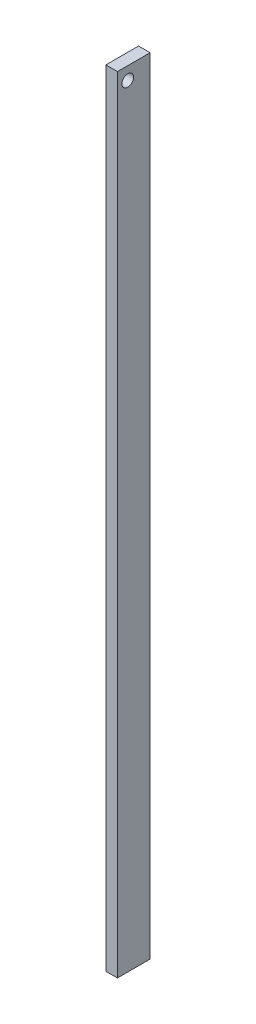
SolidWorks part; units mm, degrees
ref_plane "Alzado" through (0, 0, 0) normal (0, 0, 1) x (1, 0, 0)
ref_plane "Planta" through (0, 0, 0) normal (0, 1, 0) x (1, 0, 0)
ref_plane "Vista lateral" through (0, 0, 0) normal (1, 0, 0) x (0, 0, -1)
sketch "Sketch1" plane through (0, 0, 0) normal (0, 1, 0) x (1, 0, 0)
  line L1 (0, 0) -> (4.5, 0)
  line L2 (0, 0) -> (0, 12.7)
  line L3 (0, 12.7) -> (4.5, 12.7)
  line L4 (4.5, 0) -> (4.5, 12.7)
  dimension "D1" = 12.7
  dimension "D2" = 4.5
extrude "Boss-Extrude1" add sketch "Sketch1" along normal blind 304.8
sketch "Sketch3" plane through (0, 0, 0) normal (-1, 0, 0) x (0, 0, 1)
  line L0 (-12.7, 304.8) -> (0, 304.8) construction
  line L1 (0, 304.8) -> (0, 0) construction
  circle A0 centre (-4, 299.8) radius 2.25
  point P4 (-6.35, 304.8)
  dimension "D1" = 4.5
  dimension "D2" = 5
  dimension "D3" = 4
extrude "Cut-Extrude1" cut sketch "Sketch3" against normal through all
